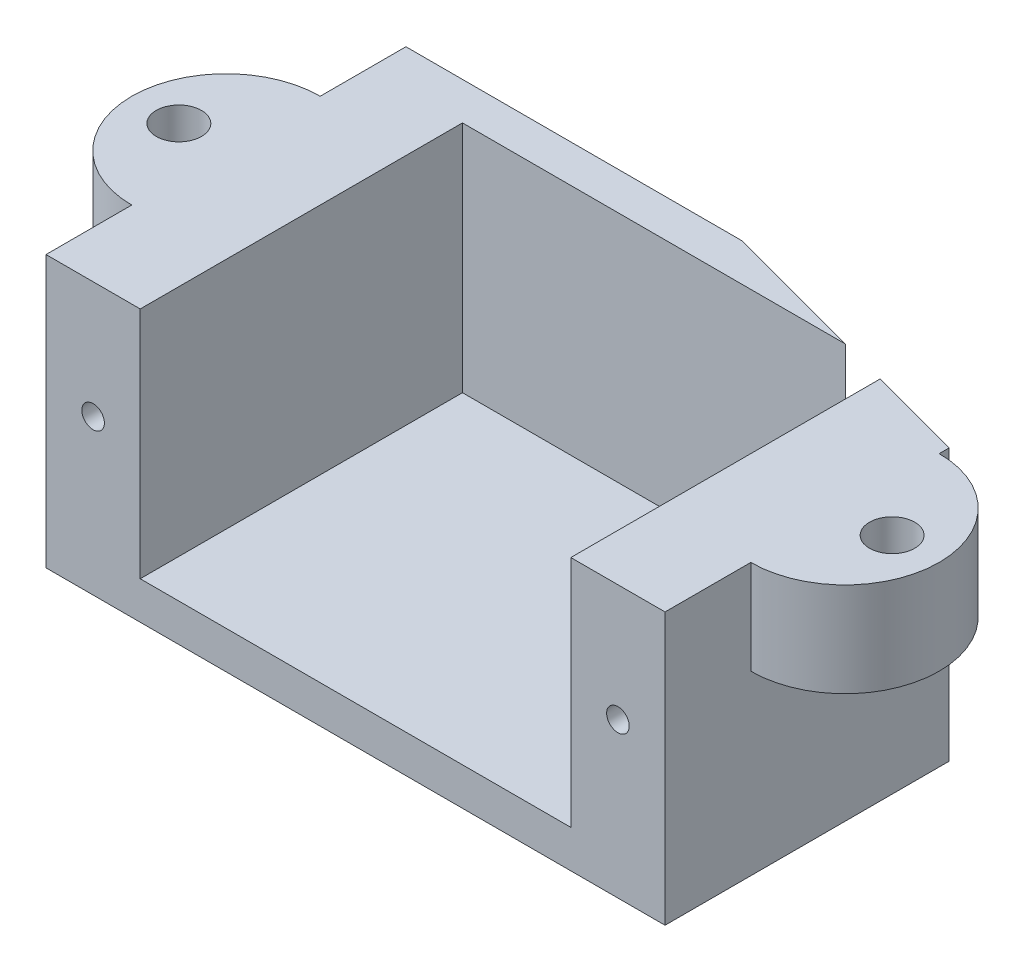
SolidWorks part; units mm, degrees
ref_plane "Piano frontale" through (0, 0, 0) normal (0, 0, 1) x (1, 0, 0)
ref_plane "Piano superiore" through (0, 0, 0) normal (0, 1, 0) x (1, 0, 0)
ref_plane "Piano destro" through (0, 0, 0) normal (1, 0, 0) x (0, 0, -1)
sketch "Schizzo1" plane through (0, 0, 0) normal (0, 0, 1) x (1, 0, 0)
  line L1 (11.425, 6.2) -> (-11.425, 6.2)
  line L2 (11.425, 6.2) -> (11.425, -6.2)
  line L3 (11.425, -6.2) -> (-11.425, -6.2)
  line L4 (-11.425, 6.2) -> (-11.425, -6.2)
  line L5 (11.425, 6.2) -> (-11.425, -6.2) construction
  line L6 (11.425, -6.2) -> (-11.425, 6.2) construction
  line L7 (16.425, 8.2) -> (-16.425, 8.2)
  line L8 (16.425, 8.2) -> (16.425, -8.2)
  line L9 (16.425, -8.2) -> (-16.425, -8.2)
  line L10 (-16.425, 8.2) -> (-16.425, -8.2)
  line L11 (16.425, 8.2) -> (-16.425, -8.2) construction
  line L12 (16.425, -8.2) -> (-16.425, 8.2) construction
  point P0 (0, 0)
  point P6 (0, 0)
  dimension "D1" = 22.85
  dimension "D2" = 12.4
  dimension "D3" = 2
  dimension "5" = 5
extrude "Estrusione-Estrusione1" add sketch "Schizzo1" along normal blind 17.1
sketch "Schizzo2" plane through (0, 0, 0) normal (0, 0, -1) x (-1, 0, 0)
  line L1 (16.425, 8.2) -> (-16.425, 8.2)
  line L2 (16.425, 8.2) -> (16.425, -8.2)
  line L3 (16.425, -8.2) -> (-16.425, -8.2)
  line L4 (-16.425, 8.2) -> (-16.425, -8.2)
  line L5 (16.425, 8.2) -> (-16.425, -8.2) construction
  line L6 (16.425, -8.2) -> (-16.425, 8.2) construction
  point P0 (0, 0)
extrude "Estrusione-Estrusione2" add sketch "Schizzo2" along normal blind 2
sketch "Schizzo5" plane through (0, 0, 17.1) normal (0, 0, 1) x (1, 0, 0)
  line L0 (-11.425, 0) -> (-13.925, 0) construction
  line L1 (-11.425, 6.2) -> (-11.425, -6.2) construction
  dimension "D1" = 2.5
hole_wizard "Foro per Vite M1-1" positions "Schizzo6" profile "Schizzo8" hole size "M1" standard "ISO"
sketch "Schizzo6" plane through (0, 0, 17.1) normal (0, 0, 1) x (1, 0, 0)
  point P0 (-13.925, 0)
sketch "Schizzo8" plane through (-13.925, 0, 17.1) normal (1, 0, 0) x (0, -1, 0)
  line L0 (0, 0) -> (0, 10.3605)
  line L1 (0, 10.3605) -> (0.6, 10)
  line L2 (0.6, 10) -> (0.6, 0)
  line L5 (0.6, 0) -> (0, 0)
  line L10 (0, 10.3605) -> (-0.6, 10) construction
  line L11 (0, -6.35) -> (0, 107.95) construction
  dimension "Hole Dia." = 1.2
  dimension "Hole Depth" = 10
  dimension "Drill Angle" = 118
mirror "Specchia1" about plane through (0, 0, 0) normal (1, 0, 0) of "Foro per Vite M1-1"
sketch "Schizzo15" plane through (0, -8.2, 0) normal (0, -1, 0) x (1, 0, 0)
  line L0 (16.425, -2) -> (1.425, -2)
  line L1 (16.425, -2) -> (-16.425, -2) construction
  line L2 (1.425, -2) -> (16.425, 2.0192)
  line L3 (16.425, 17.1) -> (16.425, -2) construction
  line L4 (16.425, 2.0192) -> (16.425, -2)
  dimension "D1" = 15
  dimension "D2" = 15
extrude "Taglio-Estrusione1" cut sketch "Schizzo15" against normal through all
sketch "Schizzo16" plane through (0, 0, 17.1) normal (0, 0, 1) x (1, 0, 0)
  line L0 (16.425, -8.2) -> (16.425, 8.2) construction
  line L1 (-16.425, 8.2) -> (16.425, 8.2)
  line L2 (-16.425, 8.2) -> (-16.425, 6.2)
  line L3 (-16.425, 6.2) -> (16.425, 6.2)
  line L4 (16.425, 8.2) -> (16.425, 6.2)
  line L5 (11.425, 6.2) -> (-11.425, 6.2) construction
extrude "Taglio-Estrusione2" cut sketch "Schizzo16" against normal up to next
sketch "Schizzo17" plane through (0, 6.2, 0) normal (0, 1, 0) x (1, 0, 0)
  line L0 (-16.425, 2) -> (-16.425, -17.1) construction
  line L1 (-16.425, -2.55) -> (-16.425, -12.55)
  arc A0 (-16.425, -2.55) -> (-16.425, -12.55) centre (-16.425, -7.55) ccw
  dimension "D1" = 10
extrude "Estrusione-Estrusione3" add sketch "Schizzo17" against normal blind 5
sketch "Schizzo18" plane through (0, 1.2, 0) normal (0, -1, 0) x (1, 0, 0)
  line L0 (-16.425, 7.55) -> (-18.925, 7.55) construction
  line L1 (-16.425, 17.1) -> (-16.425, -2) construction
  dimension "D1" = 2.5
hole_wizard "Foro per Vite M2-1" positions "Schizzo19" profile "Schizzo20" hole size "M2" standard "ISO"
sketch "Schizzo19" plane through (0, 1.2, 0) normal (0, -1, 0) x (-1, 0, 0)
  point P0 (18.925, -7.55)
sketch "Schizzo20" plane through (-18.925, 1.2, 7.55) normal (1, 0, 0) x (0, 0, -1)
  line L0 (0, 0) -> (0, 10.721)
  line L1 (0, 10.721) -> (1.2, 10)
  line L2 (1.2, 10) -> (1.2, 0)
  line L5 (1.2, 0) -> (0, 0)
  line L10 (0, 10.721) -> (-1.2, 10) construction
  line L11 (0, -6.35) -> (0, 107.95) construction
  dimension "Hole Dia." = 2.4
  dimension "Hole Depth" = 10
  dimension "Drill Angle" = 118
mirror "Specchia2" about plane through (0, 0, 0) normal (1, 0, 0) of "Estrusione-Estrusione3", "Foro per Vite M2-1"
